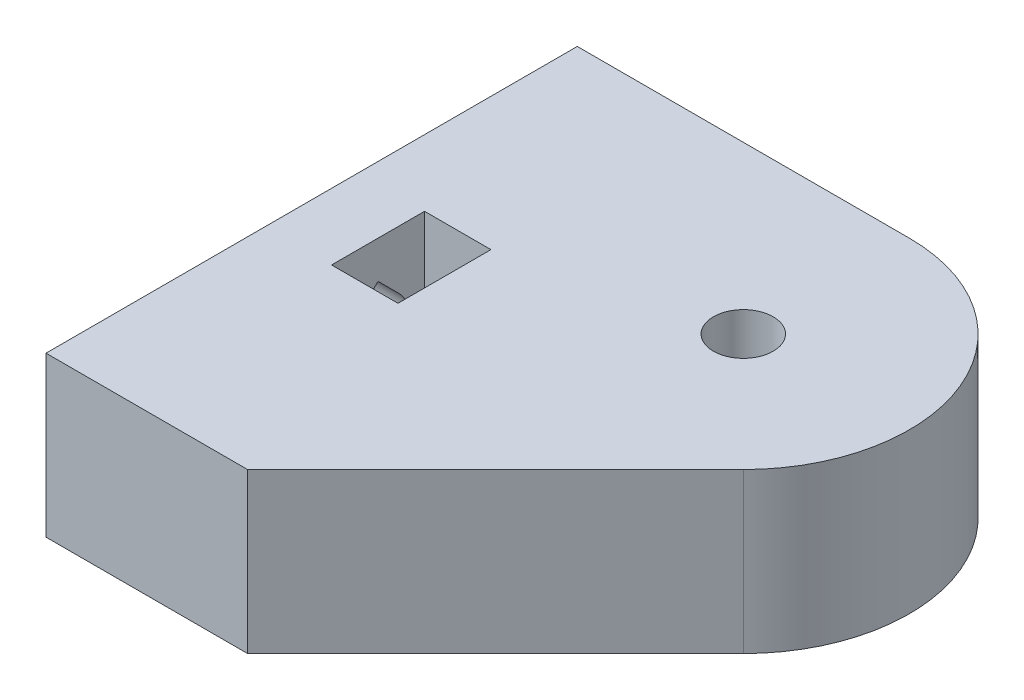
SolidWorks part; units mm, degrees
material "Printed PLA"
ref_plane "Front Plane" through (0, 0, 0) normal (0, 0, 1) x (1, 0, 0)
ref_plane "Top Plane" through (0, 0, 0) normal (0, 1, 0) x (1, 0, 0)
ref_plane "Right Plane" through (0, 0, 0) normal (1, 0, 0) x (0, 0, -1)
sketch "Sketch1" plane through (0, 0, 0) normal (0, 1, 0) x (1, 0, 0)
  line L0 (0, 12.5) -> (-15, 12.5)
  line L1 (-15, 12.5) -> (-25, 12.5)
  line L2 (-25, 12.5) -> (-25, -27.5)
  line L3 (-25, -27.5) -> (-9.8223, -27.5)
  line L4 (-9.8223, -27.5) -> (8.8388, -8.8388)
  circle A0 centre (0, 0) radius 2.25
  arc A1 (8.8388, -8.8388) -> (0, 12.5) centre (0, 0) ccw
  dimension "D1" = 4.5
  dimension "D2" = 25
  dimension "D3" = 0
  dimension "D4" = 10
  dimension "D5" = 25
  dimension "D6" = 40
  dimension "D7" = 45
extrude "Boss-Extrude1" add sketch "Sketch1" along normal blind 12
sketch "Sketch2" plane through (-25, 0, 0) normal (-1, 0, 0) x (0, 0, 1)
  line L0 (5.909, 7.591) -> (7.5, 9.182)
  line L1 (7.5, 9.182) -> (9.091, 7.591)
  line L2 (7.5, 6) -> (7.5, 9.182) construction
  line L3 (-12.5, 6) -> (27.5, 6) construction
  line L4 (-12.5, 12) -> (-12.5, 0) construction
  line L5 (27.5, 12) -> (27.5, 0) construction
  arc A0 (5.909, 7.591) -> (9.091, 7.591) centre (7.5, 6) ccw
  dimension "D1" = 4.5
extrude "Cut-Extrude1" cut sketch "Sketch2" against normal blind 20
sketch "Sketch3" plane through (0, 12, 0) normal (0, 1, 0) x (1, 0, 0)
  line L0 (-20, -7.5) -> (-25, -7.5) construction
  line L1 (-20, -4) -> (-15, -4)
  line L2 (-20, -4) -> (-20, -11)
  line L3 (-20, -11) -> (-15, -11)
  line L4 (-15, -4) -> (-15, -11)
  line L5 (-25, 12.5) -> (-25, -27.5) construction
  dimension "D1" = 5
  dimension "D2" = 5
  dimension "D3" = 7
extrude "Cut-Extrude2" cut sketch "Sketch3" against normal up to next
